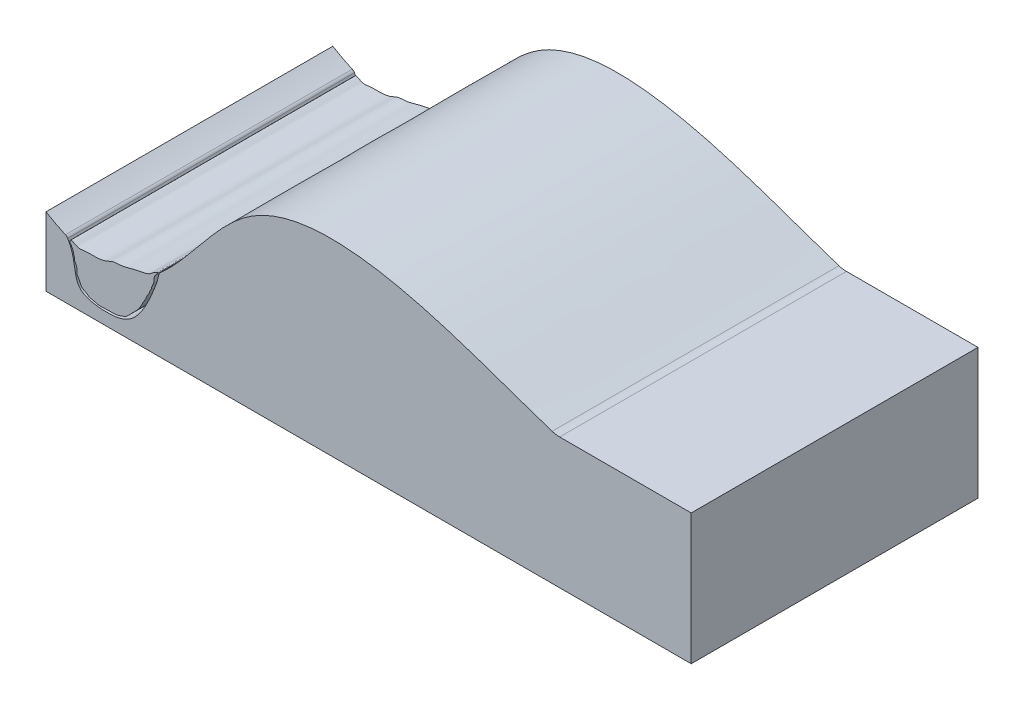
SolidWorks part; units mm, degrees
ref_plane "Front Plane" through (0, 0, 0) normal (0, 0, 1) x (1, 0, 0)
ref_plane "Top Plane" through (0, 0, 0) normal (0, 1, 0) x (1, 0, 0)
ref_plane "Right Plane" through (0, 0, 0) normal (1, 0, 0) x (0, 0, -1)
sketch "Sketch1" plane through (0, 0, 0) normal (0, 1, 0) x (1, 0, 0)
  line L1 (0, 0) -> (390144, 0)
  line L2 (0, 0) -> (0, 219456)
  line L3 (0, 219456) -> (390144, 219456)
  line L4 (390144, 0) -> (390144, 219456)
  dimension "D1" = 219456
  dimension "D2" = 390144
extrude "Boss-Extrude1" add sketch "Sketch1" along normal blind 163624.768
sketch "Sketch3" plane through (0, 0, 0) normal (0, 0, 1) x (1, 0, 0)
  line L0 (0, 163624.768) -> (0, 0) construction
  line L1 (390144, 163624.768) -> (390144, 0) construction
  line L2 (0, 52667.8814) -> (0, 163624.768)
  line L3 (0, 163624.768) -> (390144, 163624.768)
  line L4 (390144, 163624.768) -> (390144, 99964.3642)
  line L5 (0, 163624.768) -> (390144, 163624.768)
  line L6 (390144, 163624.768) -> (390144, 99964.3642)
  spline S0 degree 3 poles (0, 52667.8814) (83559.6572, 2393.5525) (133616.2869, 210787.4727) (330012.5481, 118598.2128) (390144, 99964.3642) knots 0 0 0 0 0.441082 1 1 1 1
  line M2 (390144, 0) -> (390144, 163624.768)
  line M3 (390144, 163624.768) -> (0, 163624.768)
  line M4 (0, 163624.768) -> (0, 0)
extrude "Cut-Extrude2" cut sketch "Sketch3" against normal blind 271472.66 contours S0 M4 M2 M3
sketch "Sketch5" plane through (0, 0, 0) normal (0, 0, 1) x (1, 0, 0)
  spline S0 degree 3 poles (14431.7496, 46625.0993) (24201.7274, 32802.4265) (17610.9448, 11877.3009) (53463.0961, 7585.1835) (74840.7565, 15824.6682) (91313.9035, 64441.1489) (81506.8274, 54111.2603) (76367.1066, 50845.029) (68202.5033, 44982.044) (56865.2682, 41044.1306) (45351.2439, 39680.8731) (35439.5273, 39718.4686) (25773.1918, 42444.452) (20914.1159, 42940.036) (14431.7496, 46625.0993) (24201.7274, 32802.4265) (17610.9448, 11877.3009) knots -0.072799 -0.020591 -0.008866 0 0.165559 0.282229 0.438504 0.60852 0.616398 0.649042 0.704919 0.771328 0.833559 0.884173 0.927201 0.979409 0.991134 1 1.165559 1.282229 1.438504 only from (15943.9389, 44438.8015) to (15943.9389, 44438.8015)
  spline S1 degree 3 poles (0, 52667.8814) (83559.6572, 2393.5525) (133616.2869, 210787.4727) (330012.5481, 118598.2128) (390144, 99964.3642) knots 0 0 0 0 0.441082 1 1 1 1 construction
extrude "Cut-Extrude3" cut sketch "Sketch5" against normal blind 346295.98
sketch "Sketch7" plane through (0, 0, 0) normal (0, 0, 1) x (1, 0, 0)
  spline S0 degree 3 poles (18070.7866, 41127.0455) (18475.304, 45139.2518) (23962.7542, 40353.9665) (30183.9147, 41954.9182) (37537.5175, 41407.4955) (45520.1415, 42410.2061) (51483.2006, 45890.3031) (58555.2407, 45493.8791) (65378.1529, 47875.2527) (72346.0519, 49244.944) (78836.8329, 50436.598) (81449.8345, 53125.8908) (86286.384, 55943.7922) (84079.8289, 52690.5613) (82687.65, 51130.4422) (82652.2091, 48852.6132) (82536.5595, 46912.3623) (81786.1816, 45027.4305) (80694.0976, 43387.6648) (80640.1147, 41164.4278) (79194.0938, 39860.4057) (79031.075, 37598.4746) (76995.7119, 35793.4659) (76552.9934, 32965.4592) (74618.2785, 30683.6431) (73690.9639, 28196.4723) (72158.7839, 25747.5678) (70755.1439, 23302.3136) (68431.7918, 21204.45) (66260.0756, 18679.896) (63729.2648, 16312.8745) (61435.8295, 13764.8995) (57894.7692, 12644.0029) (54454.2648, 11179.5325) (50672.1846, 11282.3295) (47077.0138, 11118.5374) (43379.5184, 11131.826) (39786.7281, 10843.9441) (36520.9118, 12108.4124) (33326.8487, 12299.9786) (30638.8272, 14774.5948) (27304.7137, 15781.2384) (26082.9072, 19021.3828) (25051.1583, 21270.8785) (23527.9885, 23006.2055) (23757.7905, 24769.5225) (23527.0895, 26476.9018) (23660.2443, 27985.5434) (22878.4594, 28895.86) (22873.704, 29744.9816) (22343.2117, 30428.7306) (21873.2078, 31131.156) (21931.726, 31903.5383) (22007.1644, 32713.1135) (21621.4709, 33635.4798) (21460.4638, 34502.1711) (21115.2633, 35254.8343) (21089.9604, 36107.5251) (20759.1419, 37218.3683) (20297.876, 38469.1216) (19537.7374, 39469.7636) (19282.2146, 40516.7158) (18070.7866, 41127.0455) (18475.304, 45139.2518) (23962.7542, 40353.9665) knots -0.020243 -0.015668 -0.009755 0 0.032228 0.056849 0.110768 0.150328 0.188551 0.220725 0.264217 0.305585 0.341894 0.362148 0.381063 0.393337 0.405061 0.419121 0.427996 0.437402 0.452166 0.459728 0.472635 0.481314 0.495358 0.514512 0.526236 0.543895 0.557839 0.573945 0.590044 0.609107 0.628816 0.647565 0.664218 0.689048 0.708581 0.725776 0.748543 0.769917 0.783892 0.805976 0.820021 0.842967 0.858762 0.873929 0.884764 0.894531 0.901514 0.913734 0.91748 0.920305 0.927164 0.931319 0.933642 0.939681 0.944531 0.949828 0.954235 0.95798 0.963726 0.973303 0.979757 0.984332 0.990245 1 1.032228 1.056849 1.110768 only from (18453.1204, 42903.9944) to (18453.1204, 42903.9944)
extrude "Boss-Extrude10" add sketch "Sketch7" against normal blind 217957.146 separate body
sketch3d "3DSketch1" plane through (0, 0, 0) normal (0, 0, 1) x (1, 0, 0)
fillet "Fillet2" radius 3810 2 edges at (86418.1627, 55180.787, -109728) (15943.9389, 44438.8015, -109728)
sketch "Sketch9" plane through (390144, 0, 0) normal (1, 0, 0) x (0, 0, -1)
  line L1 (0, 0) -> (219456, 0)
  line L2 (0, 0) -> (0, 99964.3642)
  line L3 (0, 99964.3642) -> (219456, 99964.3642)
  line L4 (219456, 0) -> (219456, 99964.3642)
extrude "Boss-Extrude12" add sketch "Sketch9" along normal blind 103579.676
fillet "Fillet4" radius 19050 1 edges at (390144, 99964.3642, -109728)
